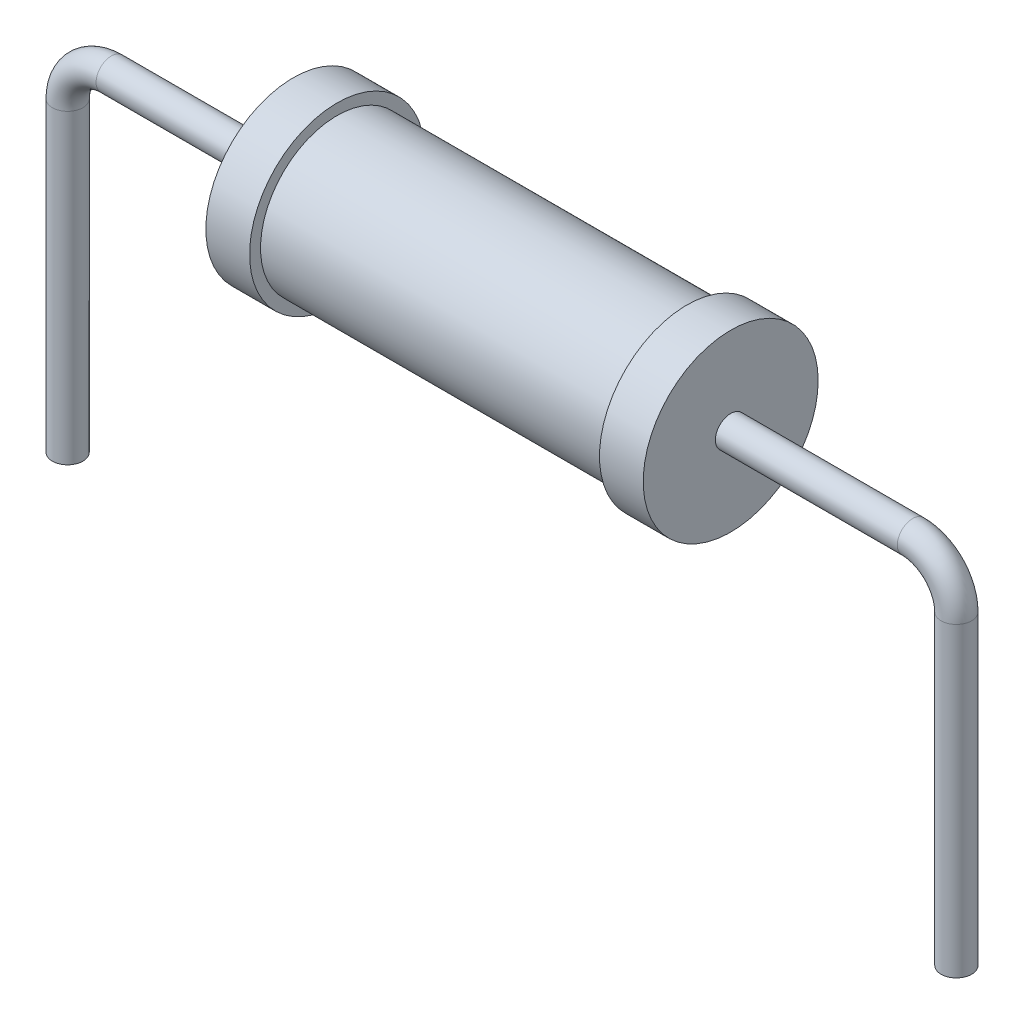
SolidWorks part; units mm, degrees
ref_plane "Спереди" through (0, 0, 0) normal (0, 0, 1) x (1, 0, 0)
ref_plane "Сверху" through (0, 0, 0) normal (0, 1, 0) x (1, 0, 0)
ref_plane "Справа" through (0, 0, 0) normal (1, 0, 0) x (0, 0, -1)
sketch "Эскиз1" plane through (0, 0, 0) normal (1, 0, 0) x (0, 0, -1)
  circle A0 centre (0, 0) radius 2
extrude "Бобышка-Вытянуть1" add sketch "Эскиз1" along normal blind 5 contours A0
sketch "Эскиз2" plane through (5, 0, 0) normal (1, 0, 0) x (0, 0, -1)
  circle A0 centre (0, 0) radius 0.35
sketch "Эскиз3" plane through (0, 0, 0) normal (0, 0, 1) x (1, 0, 0)
  line L0 (5, 0) -> (9.16, 0)
  line L1 (5, -0.35) -> (5, 0.35) construction
  line L4 (10.16, -1) -> (10.16, -8)
  arc A0 (10.16, -1) -> (9.16, 0) centre (9.16, -1) ccw
  dimension "D1" = 1
  dimension "D2" = 10.16
  dimension "D3" = 7
sweep "По траектории1" add profiles "Эскиз2" path "Эскиз3"
mirror "Зеркальное отражение1" of "По траектории1", "Бобышка-Вытянуть1"
sketch "Эскиз5" plane through (0, 0, 0) normal (1, 0, 0) x (0, 0, -1)
  circle A0 centre (0, 0) radius 1.75
extrude "Вырез-Вытянуть-Тонкостенный1" cut sketch "Эскиз5" against normal mid plane 8 thin
